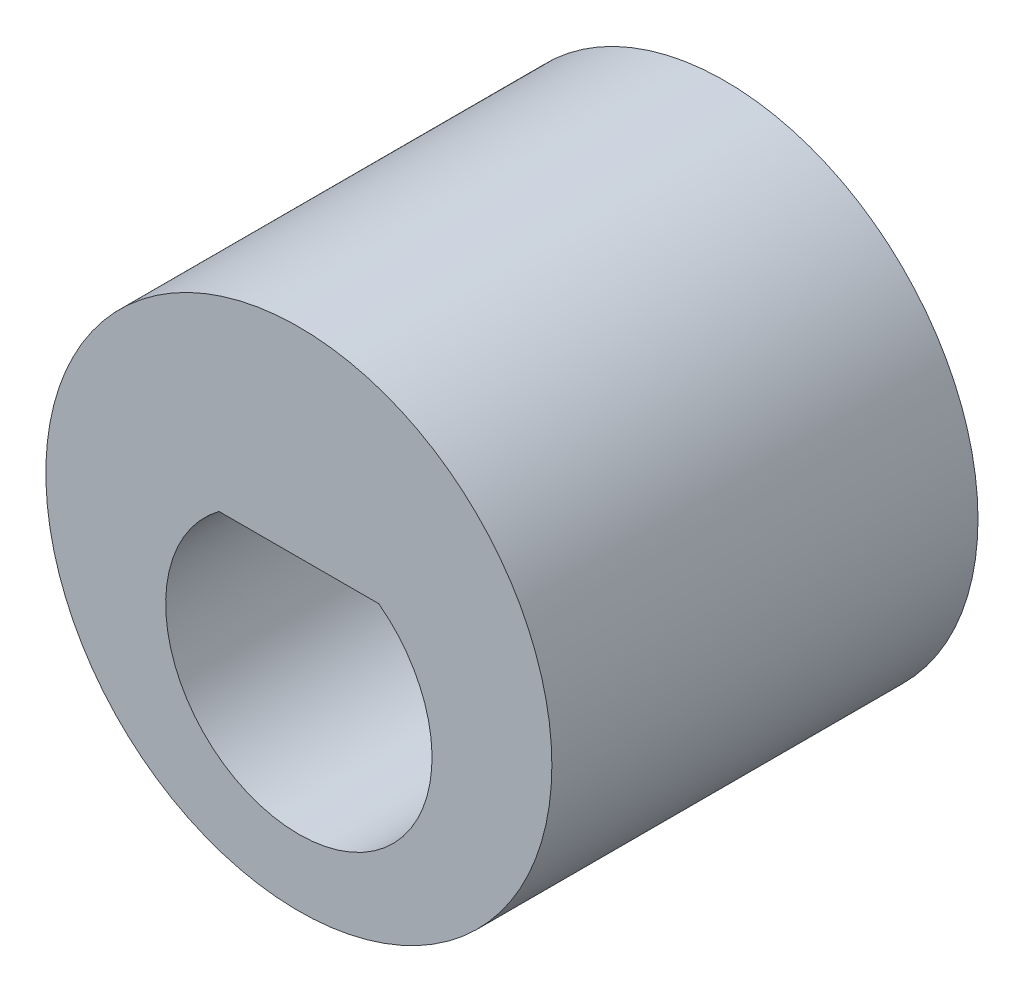
SolidWorks part; units mm, degrees
ref_plane "Plan de face" through (0, 0, 0) normal (0, 0, 1) x (1, 0, 0)
ref_plane "Plan de dessus" through (0, 0, 0) normal (0, 1, 0) x (1, 0, 0)
ref_plane "Plan de droite" through (0, 0, 0) normal (1, 0, 0) x (0, 0, -1)
sketch "Esquisse1" plane through (0, 0, 0) normal (0, 0, 1) x (1, 0, 0)
  line L0 (-1.5, 2) -> (1.5, 2)
  arc A0 (-1.5, 2) -> (1.5, 2) centre (0, 0) ccw
  circle A2 centre (0, 1) radius 4.75
  dimension "D1" = 2.5
  dimension "D2" = 2
  dimension "D4" = 9.5
  dimension "D5" = 1
extrude "Boss.-Extru.1" add sketch "Esquisse1" along normal blind 8
